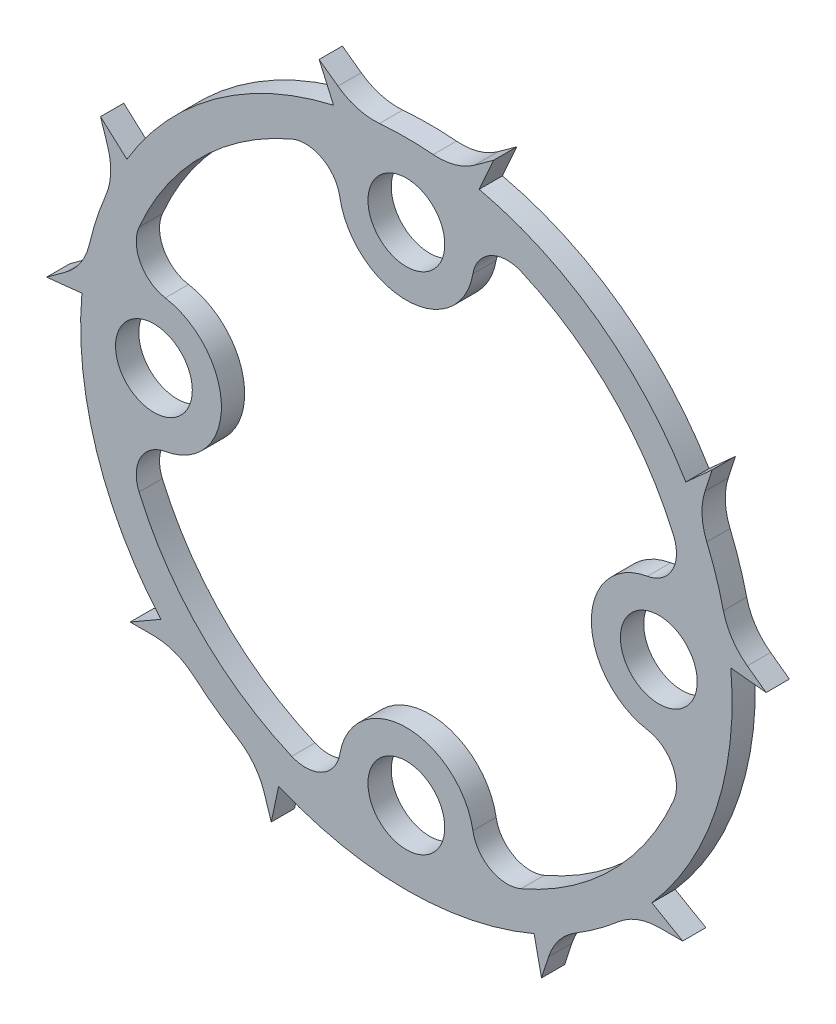
SolidWorks part; units mm, degrees
ref_plane "Front Plane" through (0, 0, 0) normal (0, 0, 1) x (1, 0, 0)
ref_plane "Top Plane" through (0, 0, 0) normal (0, 1, 0) x (1, 0, 0)
ref_plane "Right Plane" through (0, 0, 0) normal (1, 0, 0) x (0, 0, -1)
ref_plane "back of cleat" through (0, 0, 0) normal (0, 0, 1) x (1, 0, 0)
sketch "ring sketch" plane through (0, 0, 0) normal (0, 0, 1) x (1, 0, 0)
  circle A0 centre (0, 0) radius 14
  circle A1 centre (0, 0) radius 12.5
  dimension "D1" = 28
  dimension "D2" = 1.5
sketch "tooth sketch" plane through (0, 0, 0) normal (0, 0, 1) x (1, 0, 0)
  line L0 (0, 0) -> (3.75, 15.0395) construction
  line L1 (0, 0) -> (-3.75, 15.0395) construction
  line L2 (0, 0) -> (0, 15.9746) construction
  line L3 (0, 15.9746) -> (3.75, 15.0395) construction
  line L4 (3.75, 15.0395) -> (3.1294, 13.6458)
  line L5 (3.75, 15.0395) -> (2.941, 14.4518)
  line L6 (-3.75, 15.0395) -> (-3.1294, 13.6458)
  line L7 (-3.75, 15.0395) -> (-2.941, 14.4518)
  line L8 (-3.1294, 13.6458) -> (4.5345, 15.4034) construction
  circle A0 centre (0, 0) radius 15.5 construction
  circle A1 centre (0, 0) radius 14 construction
  arc A2 (-3.1294, 13.6458) -> (3.1294, 13.6458) centre (0, 0) cw
  arc A3 (-2.941, 14.4518) -> (-1.1557, 13.9522) centre (-1.3755, 16.6065) ccw
  arc A4 (2.941, 14.4518) -> (1.1557, 13.9522) centre (1.3755, 16.6065) cw
  point P11 (5.5994, 15.9023)
  point P18 (4.4062, 15.4405)
  dimension "D1" = 1.5
  dimension "D5" = 1
  dimension "D2" = 7.5
  dimension "D3" = 80
  dimension "D4" = 50
sketch "clearenc whole" plane through (0, 0, 0) normal (0, 0, 1) x (1, 0, 0)
  line L0 (0, 0) -> (0, 15.9746) construction
  circle A0 centre (0, 10.85) radius 1.65
  circle A1 centre (0, 0) radius 14 construction
  point P6 (0, 14)
  point P8 (0, 12.5)
  dimension "D2" = 3.3
  dimension "D1" = 1.5
sketch "screw sketch" plane through (0, 0, 0) normal (0, 0, 1) x (1, 0, 0)
  line L0 (4.9286, 11.4874) -> (4.9286, 13.1038)
  line L1 (-4.9286, 11.4874) -> (-4.9286, 13.1038)
  line L2 (-4.9286, 13.1038) -> (4.9286, 13.1038)
  arc A0 (-2.8586, 10.3615) -> (2.8586, 10.3615) centre (0, 10.85) ccw
  circle A1 centre (0, 10.85) radius 1.65 construction
  arc A2 (-4.9286, 11.4874) -> (-2.8586, 10.3615) centre (-4.3371, 10.1089) cw
  circle A3 centre (0, 0) radius 12.5 construction
  arc A4 (2.8586, 10.3615) -> (4.9286, 11.4874) centre (4.3371, 10.1089) cw
  circle A5 centre (0, 0) radius 14 construction
  point P1 (-5.4697, 12.8873)
  point P13 (4.8766, 13.1232)
  dimension "D1" = 1.25
  dimension "D2" = 1.5
ref_plane "front of cleat" through (0, 0, 1) normal (0, 0, 1) x (1, 0, 0)
sketch "Sketch5" plane through (0, 0, 0) normal (0, 0, 1) x (1, 0, 0)
  circle A1 centre (0, 0) radius 12.5
  circle A2 centre (0, 0) radius 12.5
  circle A3 centre (0, 0) radius 14
  circle A4 centre (0, 0) radius 14
  dimension "D1" = 0
  dimension "D2" = 0
extrude "ring" add sketch "Sketch5" along normal up to surface (1 mm away) up to plane "front of cleat"
sketch "Sketch6" plane through (0, 0, 0) normal (0, 0, 1) x (1, 0, 0)
  line L0 (-3.75, 15.0395) -> (-2.941, 14.4518) construction
  line L1 (-3.75, 15.0395) -> (-3.1294, 13.6458) construction
  line L2 (3.75, 15.0395) -> (3.1294, 13.6458) construction
  line L3 (3.75, 15.0395) -> (2.941, 14.4518) construction
  line L4 (-3.75, 15.0395) -> (-2.941, 14.4518)
  line L5 (-3.75, 15.0395) -> (-3.1294, 13.6458)
  line L6 (3.75, 15.0395) -> (3.1294, 13.6458)
  line L7 (3.75, 15.0395) -> (2.941, 14.4518)
  arc A0 (-2.941, 14.4518) -> (-1.1557, 13.9522) centre (-1.3755, 16.6065) ccw construction
  arc A1 (3.1294, 13.6458) -> (-3.1294, 13.6458) centre (0, 0) ccw construction
  arc A2 (1.1557, 13.9522) -> (2.941, 14.4518) centre (1.3755, 16.6065) ccw construction
  arc A3 (-2.941, 14.4518) -> (-1.1557, 13.9522) centre (-1.3755, 16.6065) ccw
  arc A4 (3.1294, 13.6458) -> (1.1557, 13.9522) centre (0, 0) ccw
  arc A5 (1.1557, 13.9522) -> (2.941, 14.4518) centre (1.3755, 16.6065) ccw
  arc A6 (-1.1557, 13.9522) -> (-3.1294, 13.6458) centre (0, 0) ccw
extrude "teeth" add sketch "Sketch6" along normal up to surface (1 mm away) up to plane "front of cleat"
sketch "Sketch7" plane through (0, 0, 0) normal (0, 0, 1) x (1, 0, 0)
  line L3 (4.9286, 11.4874) -> (4.9286, 13.1038)
  line L4 (-4.9286, 13.1038) -> (-4.9286, 11.4874)
  line L5 (4.9286, 13.1038) -> (-4.9286, 13.1038)
  line L6 (4.9286, 11.4874) -> (4.9286, 13.1038)
  line L7 (-4.9286, 13.1038) -> (-4.9286, 11.4874)
  line L8 (4.9286, 13.1038) -> (-4.9286, 13.1038)
  arc A3 (4.9286, 11.4874) -> (2.8586, 10.3615) centre (4.3371, 10.1089) ccw
  arc A4 (-2.8586, 10.3615) -> (2.8586, 10.3615) centre (0, 10.85) ccw
  arc A5 (-2.8586, 10.3615) -> (-4.9286, 11.4874) centre (-4.3371, 10.1089) ccw
  arc A6 (4.9286, 11.4874) -> (2.8586, 10.3615) centre (4.3371, 10.1089) ccw
  arc A7 (-2.8586, 10.3615) -> (2.8586, 10.3615) centre (0, 10.85) ccw
  arc A8 (-2.8586, 10.3615) -> (-4.9286, 11.4874) centre (-4.3371, 10.1089) ccw
  dimension "D1" = 0
extrude "screw bumps" add sketch "Sketch7" along normal up to surface (1 mm away) up to plane "front of cleat"
sketch "Sketch8" plane through (0, 0, 1) normal (0, 0, 1) x (1, 0, 0)
  circle A0 centre (0, 10.85) radius 1.65 construction
  circle A1 centre (0, 10.85) radius 1.65
extrude "screw clearence hole" cut sketch "Sketch8" against normal up to next
pattern_circular "cir pat for screws" count 4 over 360 about axis through (0, 0, 0) along (0, 0, 1) of "screw bumps", "screw clearence hole"
pattern_circular "cir.pat. teeth" count 5 over 360 about axis through (0, 0, 0) along (0, 0, 1) of "teeth"
